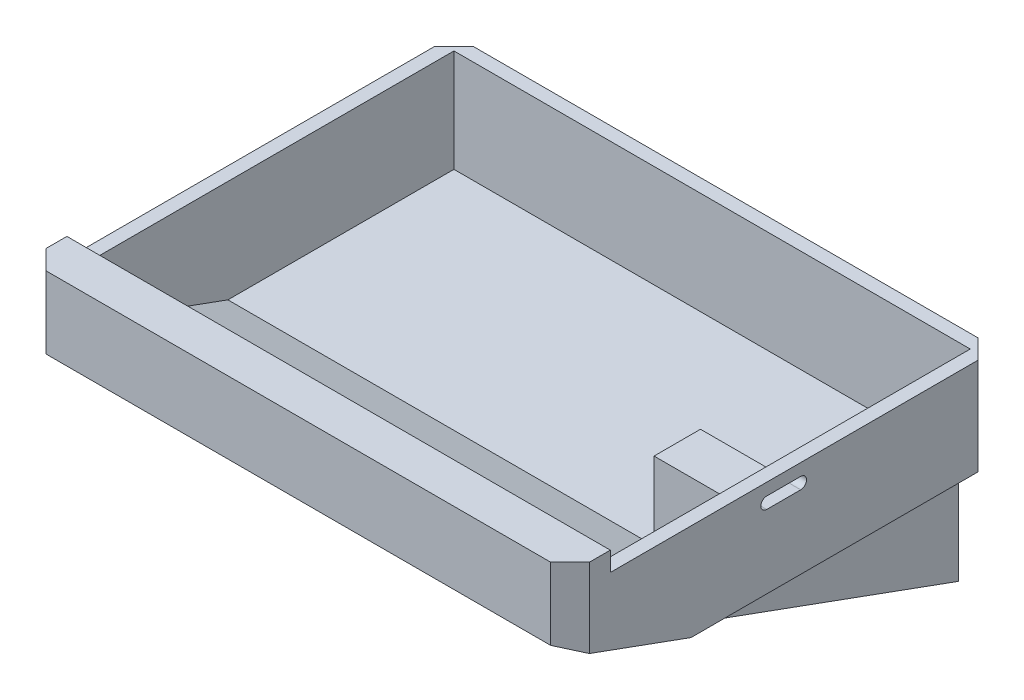
SolidWorks part; units mm, degrees
ref_plane "Front Plane" through (0, 0, 0) normal (0, 0, 1) x (1, 0, 0)
ref_plane "Top Plane" through (0, 0, 0) normal (0, 1, 0) x (1, 0, 0)
ref_plane "Right Plane" through (0, 0, 0) normal (1, 0, 0) x (0, 0, -1)
sketch "Sketch1" plane through (0, 0, 0) normal (0, 1, 0) x (1, 0, 0)
  line L1 (-70.2, -55.2) -> (70.2, -55.2)
  line L2 (-70.2, -55.2) -> (-70.2, 55.2)
  line L3 (-70.2, 55.2) -> (70.2, 55.2)
  line L4 (70.2, -55.2) -> (70.2, 55.2)
  line L5 (-70.2, -55.2) -> (70.2, 55.2) construction
  line L6 (-70.2, 55.2) -> (70.2, -55.2) construction
  point P0 (0, 0)
  dimension "D1" = 140.4
  dimension "D2" = 110.4
extrude "Boss-Extrude1" add sketch "Sketch1" against normal blind 30
shell "Shell1" thickness 3.5
sketch "Sketch2" plane through (0, 0, 0) normal (0, 1, 0) x (1, 0, 0)
  line L0 (70.2, -55.2) -> (70.2, 55.2) construction
  line L1 (-70.2, -55.2) -> (70.2, -55.2)
  line L2 (-70.2, -55.2) -> (-70.2, -44.8)
  line L3 (-70.2, -44.8) -> (70.2, -44.8)
  line L4 (70.2, -55.2) -> (70.2, -44.8)
  dimension "D1" = 10.4
extrude "Boss-Extrude2" add sketch "Sketch2" along normal blind 5
sketch "Sketch5" plane through (66.7, 0, 0) normal (-1, 0, 0) x (0, 0, 1)
  line L0 (51.7, -26.5) -> (-51.7, -26.5) construction
  line L1 (-6, -26.5) -> (6, -26.5)
  line L2 (-6, -26.5) -> (-6, -7.1)
  line L3 (-6, -7.1) -> (6, -7.1)
  line L4 (6, -26.5) -> (6, -7.1)
  line L5 (-51.7, -26.5) -> (-51.7, 0) construction
  point P6 (0, -26.5)
  dimension "D1" = 19.4
  dimension "D2" = 51.7
  dimension "D3" = 12
sketch "Sketch6" plane through (66.7, 0, 0) normal (-1, 0, 0) x (0, 0, 1)
  line L1 (-4.4, -4.6) -> (4.4, -4.6) construction
  line L2 (0, -26.5) -> (0, 0)
  line L3 (0, -26.5) -> (0, 0) construction
  line L4 (-4.4, -3.1) -> (4.4, -3.1)
  line L5 (-4.4, -6.1) -> (4.4, -6.1)
  line L7 (51.7, -26.5) -> (-51.7, -26.5) construction
  arc A0 (-4.4, -3.1) -> (-4.4, -6.1) centre (-4.4, -4.6) ccw
  arc A1 (4.4, -6.1) -> (4.4, -3.1) centre (4.4, -4.6) ccw
  point P2 (0, -4.6)
  dimension "D2" = 8.8
  dimension "D3" = 3
  dimension "D4" = 20.4
  dimension "D1" = 51.7
extrude "Cut-Extrude3" cut sketch "Sketch6" against normal blind 5
extrude "Boss-Extrude3" add sketch "Sketch5" along normal blind 24
chamfer "Chamfer1" distance 45 angle 20 2 edges at (0, -30, 55.2) (0, -26.5, 51.7)
chamfer "Chamfer3" distance 5 angle 45 7 edges at (-70.2, -4.3107, 55.2) (70.2, -30, -22.5) (-70.2, -30, -22.5) (-70.2, -15, -55.2) (0, -30, -55.2) (70.2, -15, -55.2) (70.2, -4.3107, 55.2)
ref_plane "Plane2" through (65.2, 0, 0) normal (1, 0, 0) x (0, 0, 1)
sketch "Sketch10" plane through (65.2, 0, 0) normal (1, 0, 0) x (0, 0, 1)
  line L0 (-50.2, 30) -> (10.2, 30)
  line L1 (10.2, 30) -> (-50.2, 51.9838)
  line L2 (-50.2, 51.9838) -> (-50.2, 30)
  dimension "D1" = 20
extrude "Boss-Extrude5" add sketch "Sketch10" against normal blind 5
mirror "Mirror1" about plane through (0, 0, 0) normal (1, 0, 0) of "Boss-Extrude5"
